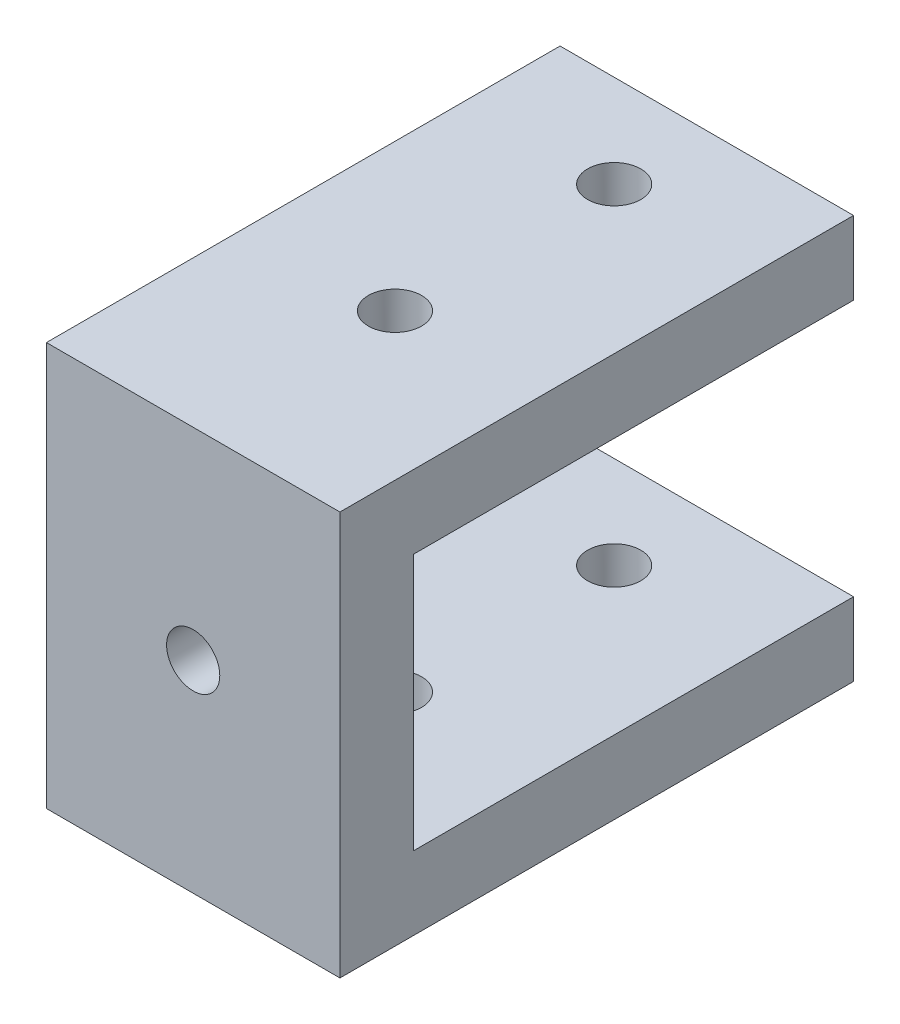
SolidWorks part; units mm, degrees
ref_plane "Front Plane" through (0, 0, 0) normal (0, 0, 1) x (1, 0, 0)
ref_plane "Top Plane" through (0, 0, 0) normal (0, 1, 0) x (1, 0, 0)
ref_plane "Right Plane" through (0, 0, 0) normal (1, 0, 0) x (0, 0, -1)
sketch "Sketch1" plane through (0, 0, 0) normal (1, 0, 0) x (0, 0, -1)
  line L0 (0, 8.89) -> (0, -8.89)
  line L1 (0, -8.89) -> (30.48, -8.89)
  line L2 (30.48, -8.89) -> (30.48, -13.97)
  line L3 (30.48, -13.97) -> (-5.08, -13.97)
  line L4 (-5.08, -13.97) -> (-5.08, 13.97)
  line L5 (-5.08, 13.97) -> (30.48, 13.97)
  line L6 (30.48, 13.97) -> (30.48, 8.89)
  line L7 (30.48, 8.89) -> (0, 8.89)
  point P8 (0, 0)
  dimension "D1" = 5.08
  dimension "D2" = 5.08
  dimension "D3" = 30.48
  dimension "D4" = 17.78
extrude "Boss-Extrude1" add sketch "Sketch1" along normal blind 20.32
sketch "Sketch2" plane through (0, 0, 5.08) normal (0, 0, 1) x (1, 0, 0)
  line L1 (20.32, 13.97) -> (20.32, -13.97) construction
  circle A0 centre (10.16, 0) radius 1.8415
  dimension "D1" = 3.683
  dimension "D2" = 10.16
extrude "Cut-Extrude1" cut sketch "Sketch2" against normal up to next
sketch "Sketch3" plane through (0, 13.97, 0) normal (0, 1, 0) x (1, 0, 0)
  line L0 (20.32, -5.08) -> (0, -5.08) construction
  line L1 (20.32, 30.48) -> (20.32, -5.08) construction
  line L2 (20.32, 30.48) -> (0, 30.48) construction
  circle A0 centre (10.16, 8.89) radius 1.8415
  circle A1 centre (10.16, 24.0665) radius 1.8415
  point P10 (0, 0)
  dimension "D1" = 3.683
  dimension "D2" = 13.97
  dimension "D3" = 10.16
  dimension "D4" = 6.4135
extrude "Cut-Extrude2" cut sketch "Sketch3" against normal through all and the other way through all
